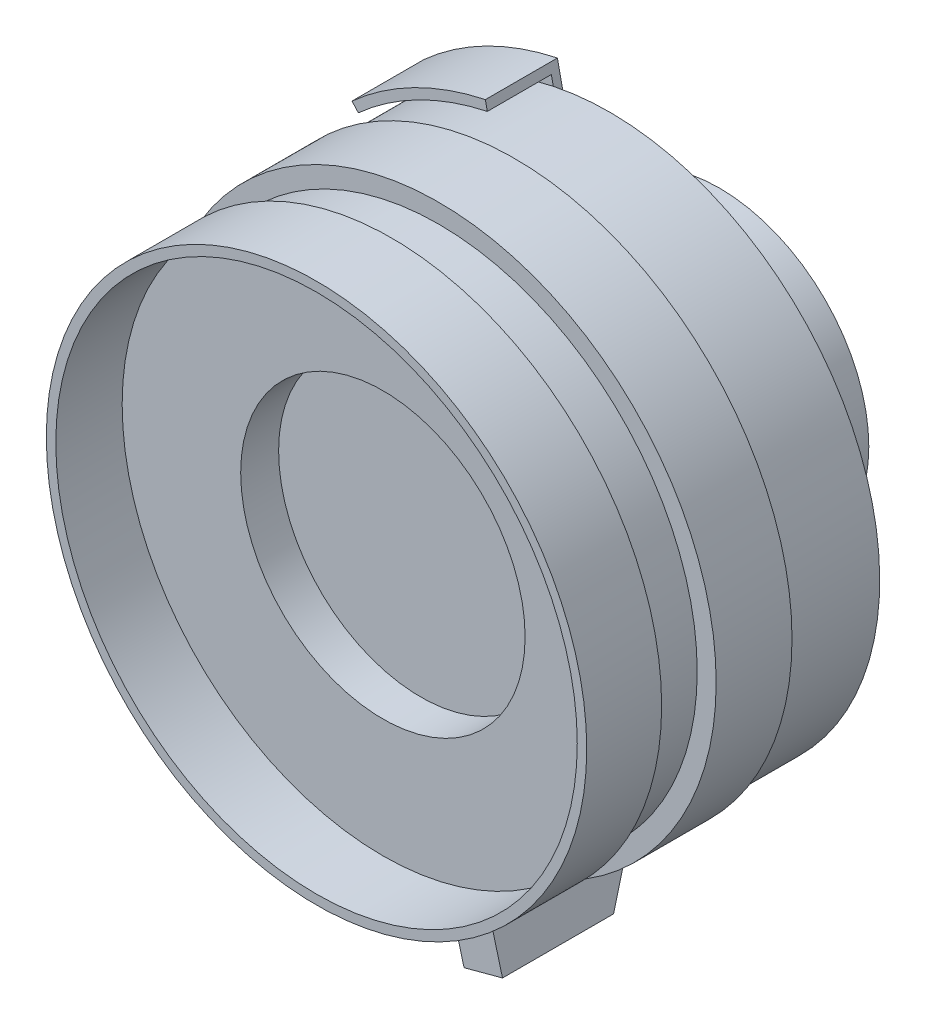
SolidWorks part; units mm, degrees
ref_plane "前视基准面" through (0, 0, 0) normal (0, 0, 1) x (1, 0, 0)
ref_plane "上视基准面" through (0, 0, 0) normal (0, 1, 0) x (1, 0, 0)
ref_plane "右视基准面" through (0, 0, 0) normal (1, 0, 0) x (0, 0, -1)
sketch "草图1" plane through (0, 0, 0) normal (0, 0, 1) x (1, 0, 0)
  circle A0 centre (0, 0) radius 15.75
  dimension "D1" = 31.5
extrude "凸台-拉伸1" add sketch "草图1" along normal blind 4.5
sketch "草图2" plane through (0, 0, 4.5) normal (0, 0, 1) x (1, 0, 0)
  circle A0 centre (0, 0) radius 16.3
  dimension "D1" = 32.6
extrude "凸台-拉伸2" add sketch "草图2" along normal blind 6
sketch "草图3" plane through (0, 0, 10.5) normal (0, 0, 1) x (1, 0, 0)
  circle A0 centre (0, 0) radius 19
  dimension "D1" = 38
extrude "凸台-拉伸3" add sketch "草图3" along normal blind 0.5
sketch "草图4" plane through (0, 0, 11) normal (0, 0, 1) x (1, 0, 0)
  circle A0 centre (0, 0) radius 24
  dimension "D1" = 48
extrude "凸台-拉伸4" add sketch "草图4" along normal blind 0.6
sketch "草图5" plane through (0, 0, 11.6) normal (0, 0, 1) x (1, 0, 0)
  circle A0 centre (0, 0) radius 28.5
  dimension "D1" = 57
extrude "凸台-拉伸5" add sketch "草图5" along normal blind 10
sketch "草图6" plane through (0, 0, 10.5) normal (0, 0, -1) x (-1, 0, 0)
  line L0 (0, 0) -> (19, 0) construction
  line L1 (4.6587, 17.3867) -> (0, 0) construction
  circle A0 centre (4.6587, 17.3867) radius 0.8
  circle A1 centre (0, 0) radius 19 construction
  dimension "D1" = 1.6
  dimension "D2" = 75
  dimension "D3" = 18
extrude "凸台-拉伸6" add sketch "草图6" along normal blind 1.2
sketch "草图7" plane through (0, 0, 21.6) normal (0, 0, 1) x (1, 0, 0)
  circle A0 centre (0, 0) radius 29.25
  dimension "D1" = 58.5
extrude "凸台-拉伸7" add sketch "草图7" along normal blind 8
sketch "草图8" plane through (0, 0, 29.6) normal (0, 0, 1) x (1, 0, 0)
  circle A0 centre (0, 0) radius 27.25
  dimension "D1" = 54.5
extrude "凸台-拉伸8" add sketch "草图8" along normal blind 5
sketch "草图9" plane through (0, 0, 34.6) normal (0, 0, 1) x (1, 0, 0)
  circle A0 centre (0, 0) radius 28.5
  dimension "D1" = 57
extrude "凸台-拉伸9" add sketch "草图9" along normal offset from surface (7.9 mm away) 42.5 up to face at (15.75, 0, 0)
sketch "草图10" plane through (0, 0, 0) normal (0, 0, -1) x (-1, 0, 0)
  circle A2 centre (0, 0) radius 14.75
  circle A3 centre (0, 0) radius 14.75
  dimension "D1" = 1
extrude "切除-拉伸1" cut sketch "草图10" against normal blind 1
sketch "草图11" plane through (0, 0, 42.5) normal (0, 0, 1) x (1, 0, 0)
  circle A0 centre (0, 0) radius 27.5
  dimension "D1" = 55
extrude "切除-拉伸2" cut sketch "草图11" against normal blind 7
sketch "草图12" plane through (0, 0, 35.5) normal (0, 0, 1) x (1, 0, 0)
  circle A0 centre (0, 0) radius 15
  dimension "D1" = 30
extrude "切除-拉伸3" cut sketch "草图12" against normal blind 4
sketch "草图13" plane through (0, 0, 11.6) normal (0, 0, -1) x (-1, 0, 0)
  line L0 (0, 0) -> (6.3411, 23.6652) construction
  line L1 (6.3413, 29.8335) -> (5.0938, 23.9646)
  line L2 (16.3937, 18.207) -> (20.4085, 22.6659)
  circle A1 centre (4.6587, 17.3867) radius 0.8 construction
  arc A2 (16.3937, 18.207) -> (5.0938, 23.9646) centre (0, 0) ccw
  arc A3 (20.4085, 22.6659) -> (6.3413, 29.8335) centre (0, 0) ccw
  circle A4 centre (0, 0) radius 28.5 construction
  point P5 (4.6587, 17.3867)
  dimension "D1" = 2
  dimension "D2" = 6
  dimension "D4" = 30
  dimension "D3" = 3
extrude "凸台-拉伸10" add sketch "草图13" along normal blind 0.85
sketch "草图14" plane through (0, 0, 11.6) normal (0, 0, 1) x (1, 0, 0)
  line L2 (-20.4085, 22.6659) -> (-19.0702, 21.1796)
  line L3 (-5.9255, 27.8772) -> (-6.3413, 29.8335)
  line L4 (-20.4085, 22.6659) -> (-19.7394, 21.9228)
  line L5 (-6.1334, 28.8554) -> (-6.3413, 29.8335)
  arc A0 (-6.1334, 28.8554) -> (-19.7394, 21.9228) centre (0, 0) ccw
  arc A2 (-5.9255, 27.8772) -> (-19.0702, 21.1796) centre (0, 0) ccw
  arc A3 (-6.3413, 29.8335) -> (-20.4085, 22.6659) centre (0, 0) ccw
  arc A5 (-6.3413, 29.8335) -> (-20.4085, 22.6659) centre (0, 0) ccw
  dimension "D2" = 1
  dimension "D1" = 0
extrude "凸台-拉伸11" add sketch "草图14" along normal offset from surface (6.75 mm away) 7.6 up to face at (-12.272, 24.0852, 10.75)
sketch "草图15" plane through (0, 0, 11) normal (0, 0, -1) x (-1, 0, 0)
  line L0 (4.6587, 17.3867) -> (-7.3763, -27.5289) construction
  line L1 (-8.2163, -22.5498) -> (-9.9224, -28.9172)
  line L2 (-9.9224, -28.9172) -> (-5.8655, -30.0043)
  line L3 (-5.8655, -30.0043) -> (-4.1594, -23.6368)
  arc A0 (5.9255, 27.8772) -> (19.0702, 21.1796) centre (0, 0) ccw construction
  circle A1 centre (0, 0) radius 24 construction
  circle A2 centre (0, 0) radius 24 construction
  arc A3 (-8.2163, -22.5498) -> (-4.1594, -23.6368) centre (0, 0) ccw
  point P12 (-7.894, -29.4607)
  dimension "D1" = 2
  dimension "D2" = 4.2
extrude "凸台-拉伸12" add sketch "草图15" against normal offset from surface (8.6 mm away) 2 up to face at (28.5, 0, 21.6)
sketch "草图16" plane through (2.0284, 0.5435, 0) normal (0.9659, 0.2588, 0) x (0, 0, -1)
  line L0 (-34.1, -25.25) -> (-34.1, -35.5)
  line L2 (-34.1, -35.5) -> (-22.3868, -35.5)
  line L3 (-22.3868, -35.5) -> (-19.5, -30.5)
  line L4 (-19.5, -30.5) -> (-19.5, -29.75)
  line L6 (-19.5, -29.75) -> (-30.1, -29.75)
  line L7 (-30.1, -29.75) -> (-30.1, -25.25)
  line L8 (-30.1, -25.25) -> (-34.1, -25.25)
  line L9 (-34.6, -28.5) -> (-34.6, 28.5) construction
  line L10 (-29.6, 29.25) -> (-29.6, -29.25) construction
  line L11 (-19.6, -30.5) -> (-11, -30.5) construction
  line L12 (-29.6, -29.25) -> (-21.6, -29.25) construction
  line L13 (-19.6, -28.4225) -> (-19.6, -30.5) construction
  line L14 (-34.6, -27.25) -> (-29.6, -27.25) construction
  dimension "D1" = 0.5
  dimension "D2" = 0.5
  dimension "D3" = 120
  dimension "D4" = 5
  dimension "D5" = 0.5
  dimension "D6" = 0.1
  dimension "D7" = 2
extrude "凸台-拉伸16" add sketch "草图16" against normal up to surface (4.2 mm away) up to face at (5.1176, -27.2129, 14.0667)
